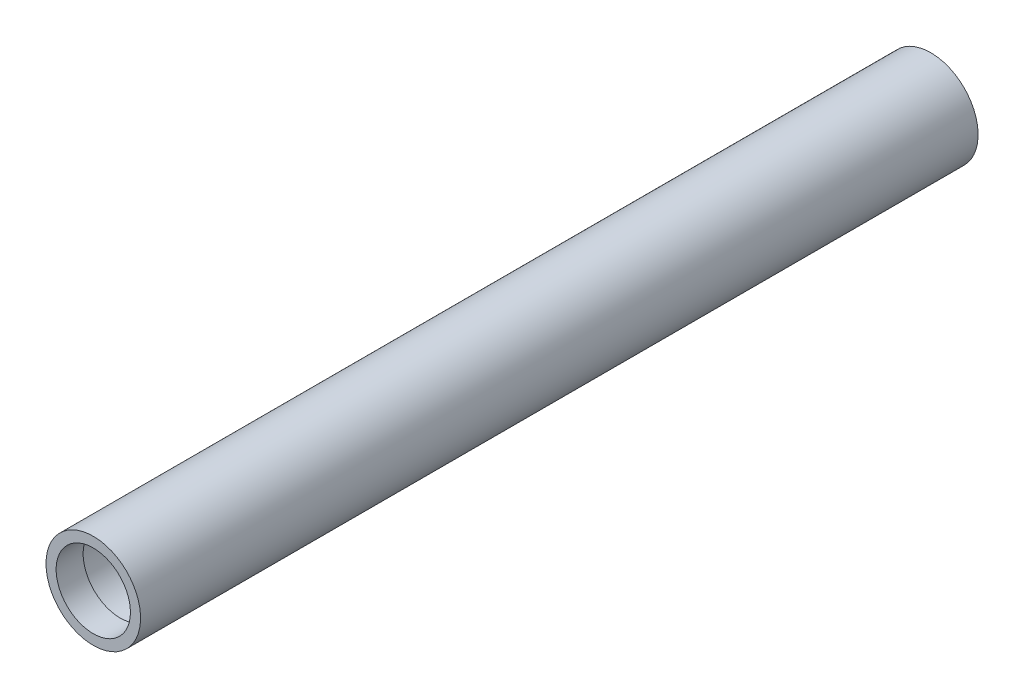
SolidWorks part; units mm, degrees
ref_plane "Front Plane" through (0, 0, 0) normal (0, 0, 1) x (1, 0, 0)
ref_plane "Top Plane" through (0, 0, 0) normal (0, 1, 0) x (1, 0, 0)
ref_plane "Right Plane" through (0, 0, 0) normal (1, 0, 0) x (0, 0, -1)
sketch "Sketch1" plane through (0, 0, 0) normal (0, 0, 1) x (1, 0, 0)
  circle A0 centre (0, 0) radius 4.445
  circle A1 centre (0, 0) radius 3.81
extrude "Boss-Extrude1" add sketch "Sketch1" along normal blind 76.2
sketch "Sketch2" plane through (0, 0, 76.2) normal (0, 0, 1) x (1, 0, 0)
  circle A0 centre (0, 0) radius 4.445
  circle A1 centre (0, 0) radius 3.4925
extrude "Boss-Extrude2" add sketch "Sketch2" along normal blind 2.54
